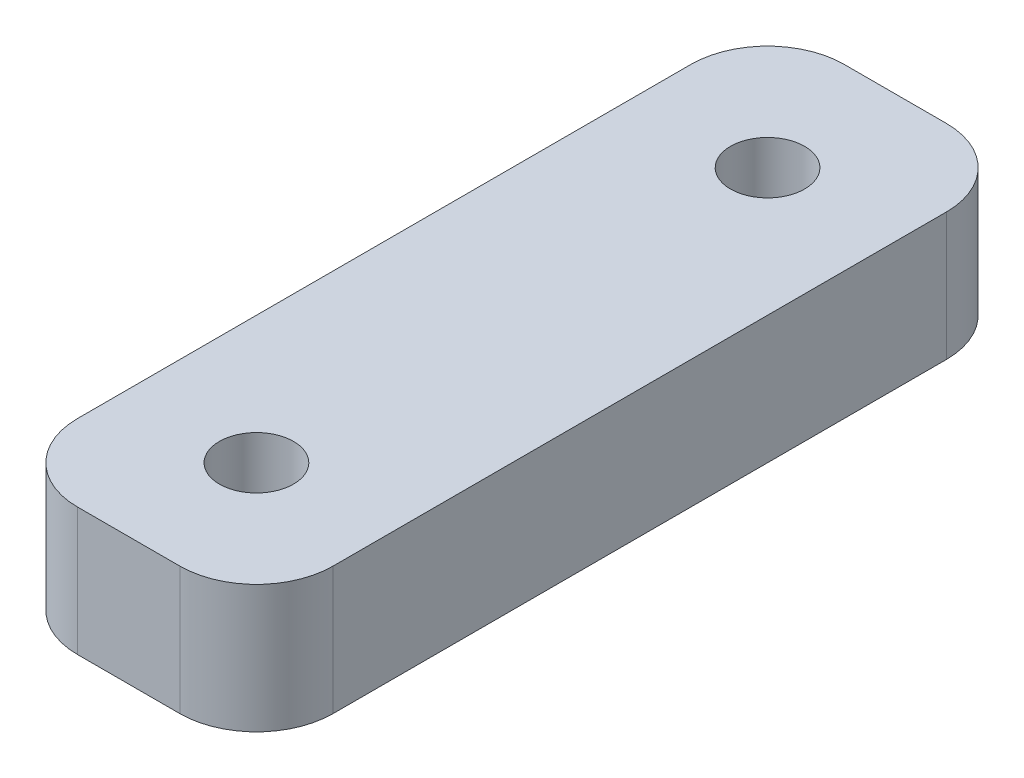
SolidWorks part; units mm, degrees
material "Oak"
ref_plane "Front Plane" through (0, 0, 0) normal (0, 0, 1) x (1, 0, 0)
ref_plane "Top Plane" through (0, 0, 0) normal (0, 1, 0) x (1, 0, 0)
ref_plane "Right Plane" through (0, 0, 0) normal (1, 0, 0) x (0, 0, -1)
sketch "Sketch1" plane through (0, 0, 0) normal (0, 1, 0) x (1, 0, 0)
  line L5 (3, 0) -> (13, 0)
  line L6 (3, 0) -> (3, 30)
  line L7 (3, 30) -> (13, 30)
  line L8 (13, 0) -> (13, 30)
  circle A0 centre (8, 25) radius 1.45
  circle A1 centre (8, 5) radius 1.45
  dimension "D3" = 2.9
  dimension "D6" = 2.9
  dimension "D1" = 30
  dimension "D2" = 10
  dimension "D4" = 5
  dimension "D5" = 5
  dimension "D7" = 5
  dimension "D8" = 5
extrude "Boss-Extrude1" add sketch "Sketch1" along normal blind 5
fillet "Fillet1" radius 3 4 edges at (13, 2.5, -30) (3, 2.5, -30) (13, 2.5, 0) (3, 2.5, 0)
